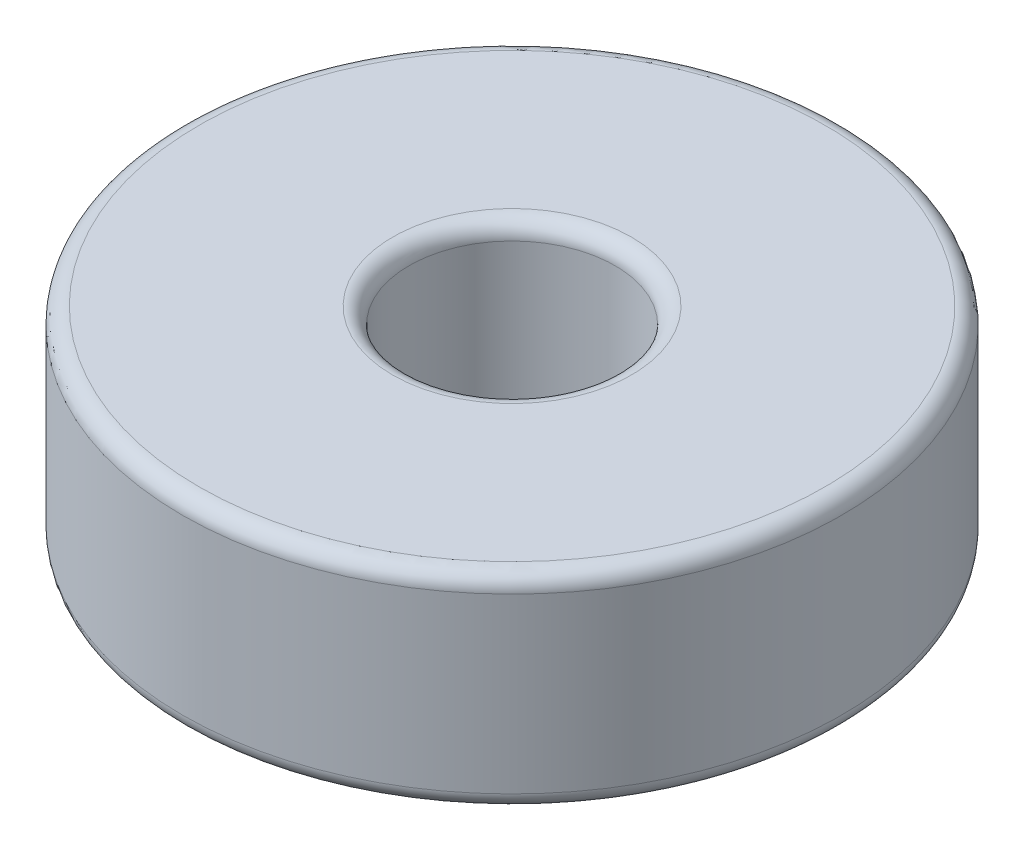
SolidWorks part; units mm, degrees
ref_plane "Front Plane" through (0, 0, 0) normal (0, 0, 1) x (1, 0, 0)
ref_plane "Top Plane" through (0, 0, 0) normal (0, 1, 0) x (1, 0, 0)
ref_plane "Right Plane" through (0, 0, 0) normal (1, 0, 0) x (0, 0, -1)
sketch "Sketch1" plane through (0, 0, 0) normal (0, 1, 0) x (1, 0, 0)
  circle A0 centre (0, 0) radius 2.5
  circle A1 centre (0, 0) radius 8
  dimension "D1" = 16
  dimension "D2" = 5
extrude "Boss-Extrude1" add sketch "Sketch1" along normal blind 5
fillet "Fillet1" radius 0.4 4 edges at (0, 0, 2.5) (0, 0, 8) (0, 5, 2.5) (0, 5, 8)
